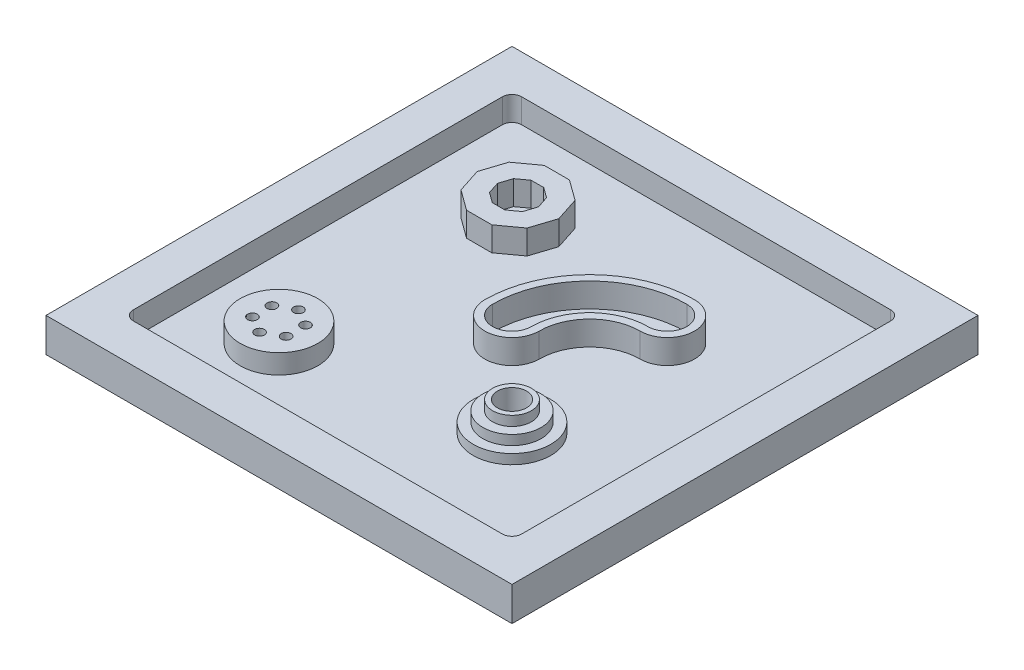
SolidWorks part; units mm, degrees
ref_plane "Front Plane" through (0, 0, 0) normal (0, 0, 1) x (1, 0, 0)
ref_plane "Top Plane" through (0, 0, 0) normal (0, 1, 0) x (1, 0, 0)
ref_plane "Right Plane" through (0, 0, 0) normal (1, 0, 0) x (0, 0, -1)
sketch "Sketch1" plane through (0, 0, 0) normal (0, 1, 0) x (1, 0, 0)
  line L0 (76.2, 152.4) -> (76.2, 0) construction
  line L1 (0, 0) -> (152.4, 0)
  line L2 (0, 0) -> (0, 152.4)
  line L3 (0, 152.4) -> (152.4, 152.4)
  line L4 (152.4, 0) -> (152.4, 152.4)
  dimension "D1" = 152.4
  dimension "D2" = 152.4
extrude "Boss-Extrude1" add sketch "Sketch1" along normal blind 11.1125
sketch "Sketch2" plane through (0, 11.1125, 0) normal (0, 1, 0) x (1, 0, 0)
  line L0 (136.525, 139.7) -> (15.875, 139.7)
  line L1 (12.7, 136.525) -> (12.7, 15.875)
  line L2 (15.875, 12.7) -> (136.525, 12.7)
  line L3 (139.7, 15.875) -> (139.7, 136.525)
  line L4 (0, 0) -> (152.4, 0)
  line L5 (152.4, 0) -> (152.4, 152.4)
  line L6 (152.4, 152.4) -> (0, 152.4)
  line L7 (0, 152.4) -> (0, 0)
  line L8 (0, 0) -> (152.4, 0) construction
  line L9 (152.4, 0) -> (152.4, 152.4) construction
  line L10 (152.4, 152.4) -> (0, 152.4) construction
  line L11 (0, 152.4) -> (0, 0) construction
  line L12 (12.7, 139.7) -> (12.7, 12.7) construction
  line L13 (12.7, 12.7) -> (139.7, 12.7) construction
  line L14 (139.7, 12.7) -> (139.7, 139.7) construction
  line L15 (139.7, 139.7) -> (12.7, 139.7) construction
  arc A0 (12.7, 15.875) -> (15.875, 12.7) centre (15.875, 15.875) ccw
  arc A1 (136.525, 12.7) -> (139.7, 15.875) centre (136.525, 15.875) ccw
  arc A2 (139.7, 136.525) -> (136.525, 139.7) centre (136.525, 136.525) ccw
  arc A3 (15.875, 139.7) -> (12.7, 136.525) centre (15.875, 136.525) ccw
  dimension "D3" = 3.175
  dimension "D1" = 0
  dimension "D2" = 12.7
extrude "Cut-Extrude1" cut sketch "Sketch2" against normal blind 7.9375
sketch "Sketch3" plane through (0, 3.175, 0) normal (0, 1, 0) x (1, 0, 0)
  line L0 (12.7, 136.525) -> (12.7, 15.875) construction
  line L1 (15.875, 12.7) -> (136.525, 12.7) construction
  circle A0 centre (38.1, 38.1) radius 12.7
  dimension "D3" = 25.4
  dimension "D1" = 25.4
  dimension "D2" = 25.4
extrude "Boss-Extrude2" add sketch "Sketch3" along normal blind 6.35
sketch "Sketch4" plane through (0, 9.525, 0) normal (0, 1, 0) x (1, 0, 0)
  circle A0 centre (38.1, 38.1) radius 12.7 construction
  circle A1 centre (38.1, 38.1) radius 12.7 construction
  circle A2 centre (38.1, 44.45) radius 1.5875
  circle A3 centre (43.5993, 41.275) radius 1.5875
  circle A4 centre (43.5993, 34.925) radius 1.5875
  circle A5 centre (38.1, 31.75) radius 1.5875
  circle A6 centre (32.6007, 34.925) radius 1.5875
  circle A7 centre (32.6007, 41.275) radius 1.5875
  dimension "D1" = 3.175
  dimension "D2" = 6.35
extrude "Cut-Extrude2" cut sketch "Sketch4" against normal up to surface (6.35 mm away) up to face at (76.2, 3.175, -76.2)
sketch "Sketch5" plane through (0, 3.175, 0) normal (0, 1, 0) x (1, 0, 0)
  line L0 (136.525, 139.7) -> (15.875, 139.7) construction
  line L1 (53.9181, 103.404) -> (56.4684, 111.253)
  line L2 (56.4684, 111.253) -> (53.9181, 119.1021)
  line L3 (53.9181, 119.1021) -> (47.2413, 123.953)
  line L4 (47.2413, 123.953) -> (38.9884, 123.953)
  line L5 (38.9884, 123.953) -> (32.3116, 119.1021)
  line L6 (32.3116, 119.1021) -> (29.7613, 111.253)
  line L7 (29.7613, 111.253) -> (32.3116, 103.404)
  line L8 (32.3116, 103.404) -> (38.9884, 98.553)
  line L9 (38.9884, 98.553) -> (47.2413, 98.553)
  line L10 (47.2413, 98.553) -> (53.9181, 103.404)
  line L11 (49.7916, 111.253) -> (48.5165, 115.1776)
  line L12 (48.5165, 115.1776) -> (45.1781, 117.603)
  line L13 (45.1781, 117.603) -> (41.0516, 117.603)
  line L14 (41.0516, 117.603) -> (37.7132, 115.1776)
  line L15 (37.7132, 115.1776) -> (36.4381, 111.253)
  line L16 (36.4381, 111.253) -> (37.7132, 107.3285)
  line L17 (37.7132, 107.3285) -> (41.0516, 104.903)
  line L18 (41.0516, 104.903) -> (45.1781, 104.903)
  line L19 (45.1781, 104.903) -> (48.5165, 107.3285)
  line L20 (48.5165, 107.3285) -> (49.7916, 111.253)
  circle A0 centre (43.1148, 111.253) radius 12.7 construction
  circle A1 centre (43.1148, 111.253) radius 6.35 construction
  dimension "D1" = 25.4
  dimension "D2" = 12.7
extrude "Boss-Extrude3" add sketch "Sketch5" along normal up to surface (7.9375 mm away) up to face at (76.2, 11.1125, -76.2)
sketch "Sketch6" plane through (0, 3.175, 0) normal (0, 1, 0) x (1, 0, 0)
  line L0 (136.525, 139.7) -> (15.875, 139.7) construction
  line L1 (139.7, 15.875) -> (139.7, 136.525) construction
  line L2 (101.6, 76.2) -> (101.6, 107.95) construction
  line L3 (101.6, 76.2) -> (69.85, 76.2) construction
  circle A0 centre (101.6, 76.2) radius 19.05 construction
  circle A1 centre (101.6, 76.2) radius 31.75 construction
  circle A2 centre (101.6, 76.2) radius 25.4 construction
  circle A3 centre (101.6, 101.6) radius 6.35 construction
  circle A4 centre (76.2, 76.2) radius 6.35 construction
  arc A5 (101.6, 95.25) -> (82.55, 76.2) centre (101.6, 76.2) ccw
  arc A6 (101.6, 107.95) -> (69.85, 76.2) centre (101.6, 76.2) ccw
  arc A7 (69.85, 76.2) -> (82.55, 76.2) centre (76.2, 76.2) ccw
  arc A8 (101.6, 107.95) -> (101.6, 95.25) centre (101.6, 101.6) cw
  dimension "D1" = 38.1
  dimension "D3" = 63.5
  dimension "D4" = 38.1
  dimension "D2" = 12.7
  dimension "D5" = 6.35
extrude "Extrude-Thin6" add sketch "Sketch6" along normal up to surface (7.9375 mm away) thin contours A8 A6 A7 A5 up to face at (76.2, 11.1125, -76.2) thin type one direction wall 2.54
sketch "Sketch8" plane through (0, 3.175, 0) normal (0, 1, 0) x (1, 0, 0)
  line L0 (139.7, 15.875) -> (139.7, 136.525) construction
  line L1 (15.875, 12.7) -> (136.525, 12.7) construction
  circle A0 centre (101.6, 50.8) radius 12.7
  dimension "D1" = 25.4
  dimension "D2" = 38.1
  dimension "D3" = 38.1
extrude "Boss-Extrude4" add sketch "Sketch8" along normal blind 3.175
sketch "Sketch9" plane through (0, 6.35, 0) normal (0, 1, 0) x (1, 0, 0)
  circle A0 centre (101.6, 50.8) radius 9.525
  circle A1 centre (101.6, 50.8) radius 12.7 construction
  circle A2 centre (101.6, 50.8) radius 12.7 construction
  dimension "D1" = 19.05
extrude "Boss-Extrude5" add sketch "Sketch9" along normal blind 3.175
sketch "Sketch10" plane through (0, 9.525, 0) normal (0, 1, 0) x (1, 0, 0)
  circle A0 centre (101.6, 50.8) radius 9.525 construction
  circle A1 centre (101.6, 50.8) radius 9.525 construction
  circle A2 centre (101.6, 50.8) radius 6.35
  dimension "D1" = 12.7
extrude "Boss-Extrude6" add sketch "Sketch10" along normal blind 3.175
sketch "Sketch11" plane through (0, 12.7, 0) normal (0, 1, 0) x (1, 0, 0)
  circle A0 centre (101.6, 50.8) radius 4.7625
  dimension "D1" = 9.525
extrude "Cut-Extrude3" cut sketch "Sketch11" against normal blind 10.16
ref_plane "Plane1" through (0, 12.7, 0) normal (0, 1, 0) x (1, 0, 0)
sketch "Sketch13" plane through (0, 12.7, 0) normal (0, 1, 0) x (1, 0, 0)
  line L4 (0, 152.4) -> (0, 0)
  line L5 (0, 0) -> (152.4, 0)
  line L6 (152.4, 0) -> (152.4, 152.4)
  line L7 (152.4, 152.4) -> (0, 152.4)
  line L8 (0, 152.4) -> (0, 0)
  line L9 (0, 0) -> (152.4, 0)
  line L10 (152.4, 0) -> (152.4, 152.4)
  line L11 (152.4, 152.4) -> (0, 152.4)
  dimension "D1" = 0
ref_point "Point1"
